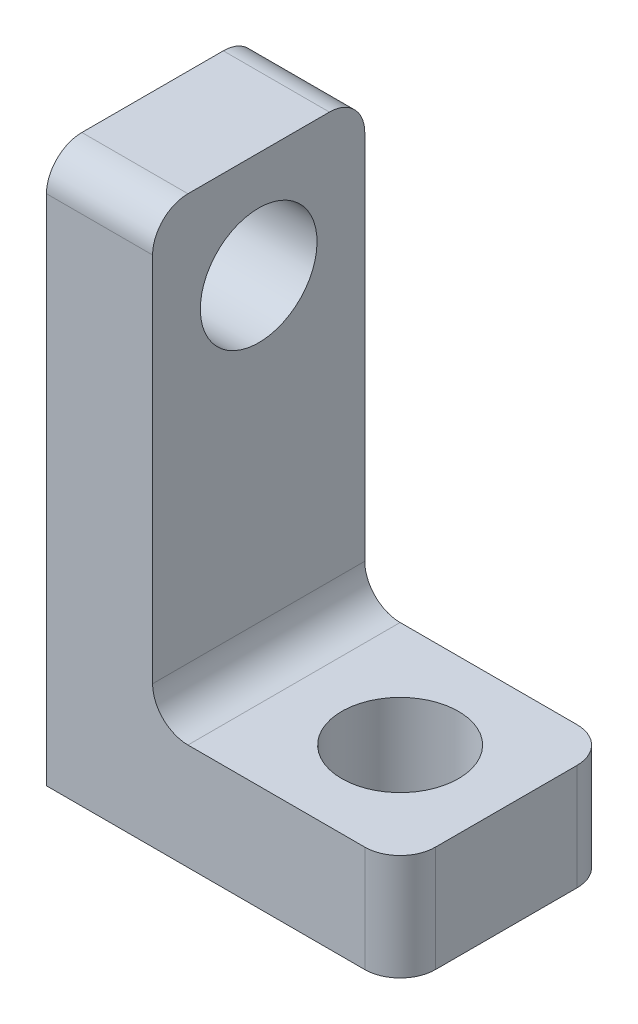
SolidWorks part; units mm, degrees
material "ABS"
ref_plane "前视基准面" through (0, 0, 0) normal (0, 0, 1) x (1, 0, 0)
ref_plane "上视基准面" through (0, 0, 0) normal (0, 1, 0) x (1, 0, 0)
ref_plane "右视基准面" through (0, 0, 0) normal (1, 0, 0) x (0, 0, -1)
sketch "草图1" plane through (0, 0, 0) normal (0, 0, 1) x (1, 0, 0)
  line L0 (10, 0) -> (0, 0)
  line L1 (0, 0) -> (0, 15.5)
  line L2 (0, 15.5) -> (3, 15.5)
  line L3 (3, 15.5) -> (3, 3)
  line L4 (3, 3) -> (10, 3)
  line L5 (10, 3) -> (10, 0)
  dimension "D1" = 10
  dimension "D2" = 3
  dimension "D3" = 15.5
extrude "凸台-拉伸1" add sketch "草图1" along normal blind 6
sketch "草图2" plane through (3, 0, 0) normal (1, 0, 0) x (0, 0, -1)
  line L0 (-6, 3) -> (-6, 15.5) construction
  line L1 (-6, 15.5) -> (0, 15.5) construction
  circle A0 centre (-3, 12.5) radius 1.65
  dimension "D1" = 3.3
  dimension "D2" = 3
  dimension "D3" = 3
extrude "切除-拉伸1" cut sketch "草图2" against normal blind 6
sketch "草图3" plane through (0, 3, 0) normal (0, 1, 0) x (1, 0, 0)
  line L0 (10, -6) -> (3, -6) construction
  line L1 (10, -6) -> (10, 0) construction
  circle A0 centre (7, -3) radius 1.65
  dimension "D1" = 3.3
  dimension "D2" = 3
  dimension "D3" = 3
extrude "切除-拉伸2" cut sketch "草图3" against normal blind 6
fillet "圆角1" radius 1 5 edges at (10, 1.5, 0) (10, 1.5, 6) (1.5, 15.5, 0) (1.5, 15.5, 6) (3, 3, 3)
